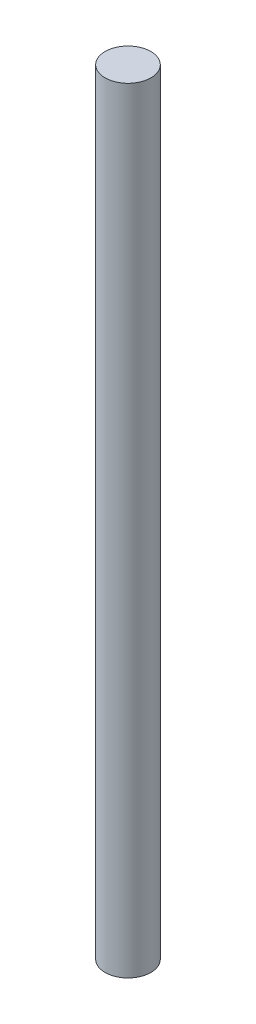
SolidWorks part; units mm, degrees
ref_plane "Front Plane" through (0, 0, 0) normal (0, 0, 1) x (1, 0, 0)
ref_plane "Top Plane" through (0, 0, 0) normal (0, 1, 0) x (1, 0, 0)
ref_plane "Right Plane" through (0, 0, 0) normal (1, 0, 0) x (0, 0, -1)
sketch "Sketch1" plane through (0, 0, 0) normal (0, 1, 0) x (1, 0, 0)
  circle A0 centre (0, 0) radius 14.75
  dimension "D1" = 29.5
extrude "Boss-Extrude1" add sketch "Sketch1" along normal blind 500
